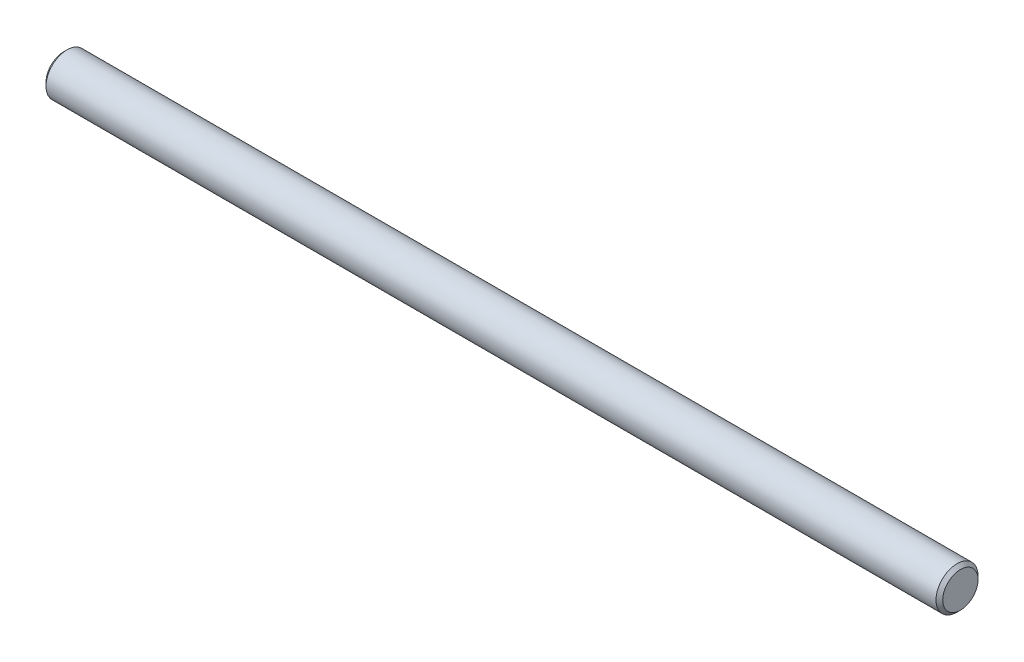
SolidWorks part; units mm, degrees
material "AISI 304"
ref_plane "Front" through (0, 0, 0) normal (0, 0, 1) x (1, 0, 0)
ref_plane "Top" through (0, 0, 0) normal (0, 1, 0) x (1, 0, 0)
ref_plane "Right" through (0, 0, 0) normal (1, 0, 0) x (0, 0, -1)
sketch "Sketch1" plane through (0, 0, 0) normal (1, 0, 0) x (0, 0, -1)
  circle A0 centre (0, 0) radius 2.3812
  dimension "D1" = 4.7625
extrude "Extrude1" add sketch "Sketch1" along normal blind 101.6
chamfer "Chamfer1" distance 0.381 angle 45 2 edges at (0, 0, -2.3812) (101.6, 0, -2.3812)
